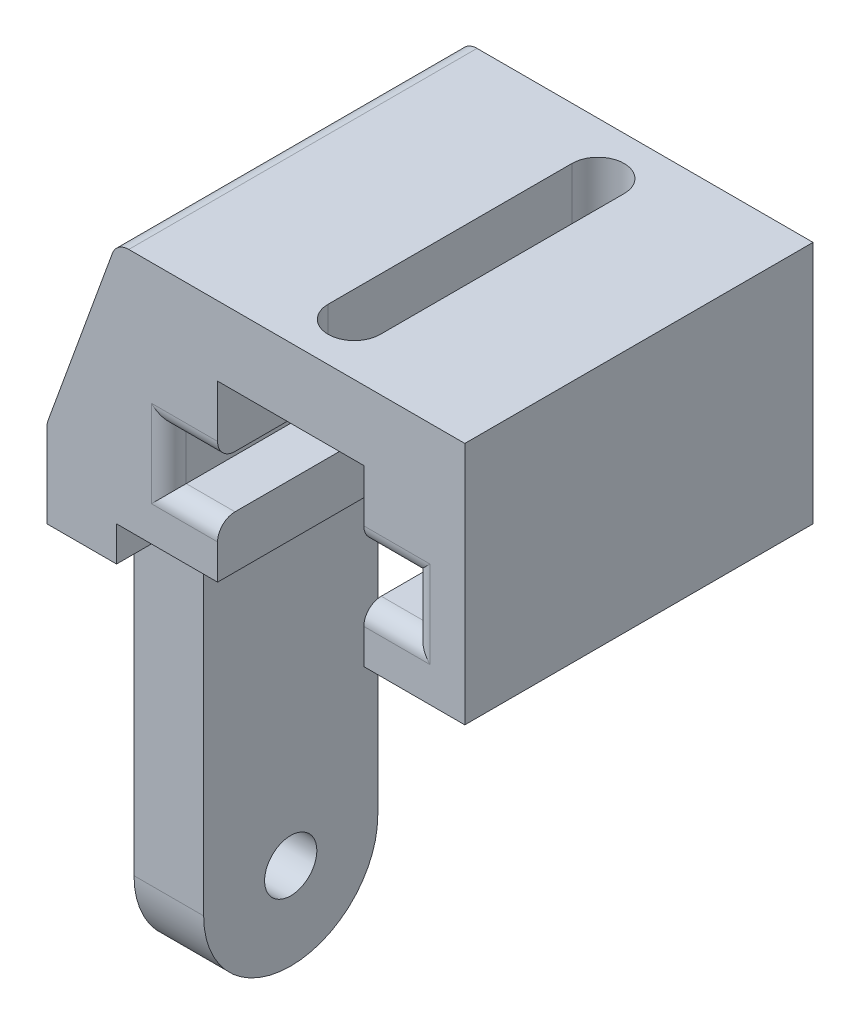
SolidWorks part; units mm, degrees
ref_plane "前视基准面" through (0, 0, 0) normal (0, 0, 1) x (1, 0, 0)
ref_plane "上视基准面" through (0, 0, 0) normal (0, 1, 0) x (1, 0, 0)
ref_plane "右视基准面" through (0, 0, 0) normal (1, 0, 0) x (0, 0, -1)
sketch "草图1" plane through (0, 0, 0) normal (0, 0, 1) x (1, 0, 0)
  line L0 (0, 0) -> (0, 14) construction
  line L11 (5.8, 6) -> (3, 6)
  line L12 (3, 6) -> (3, 3)
  line L13 (3, 3) -> (5.8, 3)
  line L14 (5.8, 3) -> (5.8, 0)
  line L15 (5.8, 0) -> (0, 0)
  line L16 (10, 17.7242) -> (10, -8.7509) construction
  line L17 (14.2, 0) -> (20, 0)
  line L18 (14.2, 3) -> (14.2, 0)
  line L19 (17, 3) -> (14.2, 3)
  line L20 (17, 6) -> (17, 3)
  line L21 (14.2, 6) -> (17, 6)
  line L23 (20, 0) -> (20, 14)
  line L27 (20, 14) -> (0, 14)
  line L28 (5.8, 6) -> (5.8, 10)
  line L29 (5.8, 10) -> (14.2, 10)
  line L30 (14.2, 10) -> (14.2, 6)
  line L33 (-4, 3) -> (-4, -2)
  line L34 (-4, -2) -> (0, -2)
  line L35 (0, -2) -> (0, 0)
  line L36 (0, 14) -> (-4, 3)
  point P22 (10, 9.8)
  point P23 (10, 9.8)
  dimension "D1" = 8
  dimension "D2" = 3
  dimension "D3" = 14
  dimension "D4" = 4
  dimension "D5" = 4
  dimension "D6" = 3
  dimension "D7" = 5.8
  dimension "D8" = 2
  dimension "D9" = 20
extrude "凸台-拉伸1" add sketch "草图1" along normal blind 20
sketch "草图2" plane through (-4, 0, 0) normal (-1, 0, 0) x (0, 0, 1)
  line L0 (20, -2) -> (0, -2) construction
  line L1 (5, -2) -> (15, -2)
  line L2 (5, -2) -> (5, -22)
  line L4 (15, -2) -> (15, -22)
  line L5 (0, 3) -> (0, -2) construction
  line L10 (10, -2) -> (10, -27.9019) construction
  line L11 (20, 0) -> (0, 0) construction
  arc A0 (5, -22) -> (15, -22) centre (10, -22) ccw
  circle A1 centre (10, -22) radius 1.5
  dimension "D3" = 3
  dimension "D1" = 10
  dimension "D2" = 5
  dimension "D4" = 22
extrude "凸台-拉伸2" add sketch "草图2" against normal up to surface (4 mm away) up to face at (0, -1, 10)
fillet "圆角6" radius 1 14 edges at (3, 4.5, 0) (4.4, 3, 0) (15.6, 3, 0) (17, 4.5, 0) (4.4, 3, 20) (15.6, 3, 20) (17, 4.5, 20) (3, 4.5, 20) (15.6, 6, 0) (4.4, 6, 0) (15.6, 6, 20) (4.4, 6, 20) (-4, 3, 10) (0, 14, 10)
sketch "草图3" plane through (0, 14, 0) normal (0, 1, 0) x (1, 0, 0)
  line L0 (10.6502, 0.9633) -> (10.6502, -18.0334) construction
  line L1 (20, 0) -> (0.7004, 0) construction
  line L2 (20, -20) -> (0.7004, -20) construction
  line L3 (9.1502, -3) -> (9.1502, -17)
  line L4 (12.1502, -3) -> (12.1502, -17)
  arc A0 (12.1502, -3) -> (9.1502, -3) centre (10.6502, -3) ccw
  arc A1 (9.1502, -17) -> (12.1502, -17) centre (10.6502, -17) ccw
  dimension "D1" = 3
  dimension "D3" = 3
  dimension "D2" = 3
  dimension "D4" = 3
extrude "切除-拉伸1" cut sketch "草图3" against normal up to next
